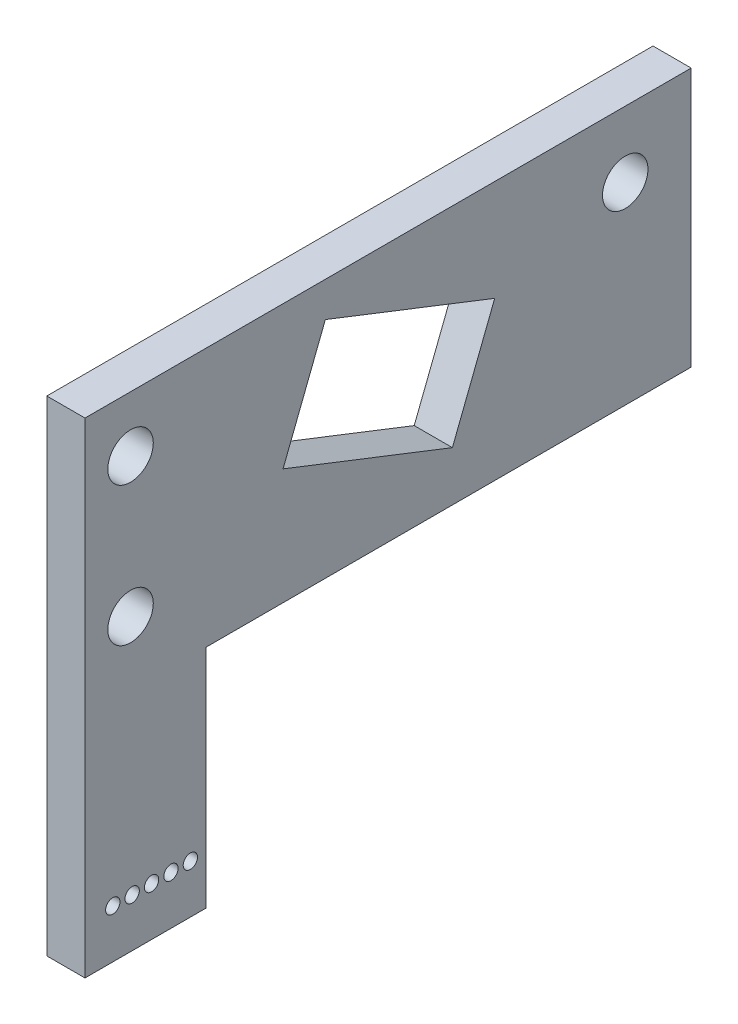
SolidWorks part; units mm, degrees
ref_plane "Front Plane" through (0, 0, 0) normal (0, 0, 1) x (1, 0, 0)
ref_plane "Top Plane" through (0, 0, 0) normal (0, 1, 0) x (1, 0, 0)
ref_plane "Right Plane" through (0, 0, 0) normal (1, 0, 0) x (0, 0, -1)
sketch "Sketch1" plane through (0, 0, 0) normal (1, 0, 0) x (0, 0, -1)
  line L0 (6.9096, 6.9096) -> (-56.5904, 6.9096)
  line L1 (-56.5904, 6.9096) -> (-56.5904, -43.8904)
  line L2 (-56.5904, -43.8904) -> (-43.8904, -43.8904)
  line L3 (-43.8904, -43.8904) -> (-43.8904, -20.2221)
  line L4 (-43.8904, -20.2221) -> (6.9096, -20.2221)
  line L5 (6.9096, -20.2221) -> (6.9096, 6.9096)
  line L6 (0, 6.9096) -> (0, 0) construction
  line L7 (6.9096, 0) -> (0, 0) construction
  line L8 (-31.4133, 3.2507) -> (-13.6731, -3.6911)
  line L9 (-31.4133, 3.2507) -> (-35.8457, -8.0765)
  line L10 (-13.6731, -3.6911) -> (-18.1055, -15.0183)
  line L11 (-35.8457, -8.0765) -> (-18.1055, -15.0183)
  line L12 (-45.553, -38.8104) -> (-47.585, -38.8104) construction
  circle A0 centre (0, 0) radius 2.3813
  circle A1 centre (-45.553, -38.8104) radius 0.75
  circle A2 centre (-47.585, -38.8104) radius 0.75
  circle A3 centre (-49.617, -38.8104) radius 0.75
  circle A4 centre (-51.649, -38.8104) radius 0.75
  circle A5 centre (-51.8181, -13.4841) radius 2.3812
  circle A6 centre (-51.8181, 1.0794) radius 2.3812
  circle A7 centre (-53.681, -38.8104) radius 0.75
  dimension "D1" = 4.7625
  dimension "D2" = 1.5
  dimension "D3" = 5.08
  dimension "D5" = 2.032
  dimension "D4" = 5
extrude "Boss-Extrude1" add sketch "Sketch1" along normal mid plane 4
